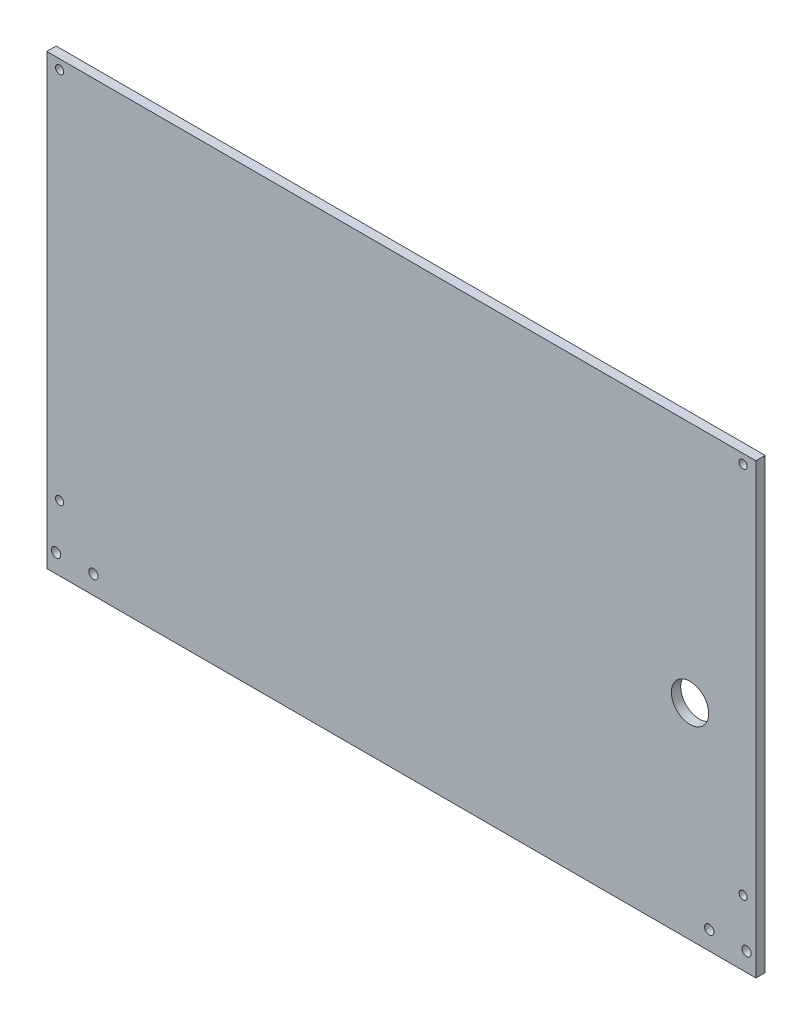
SolidWorks part; units mm, degrees
ref_plane "Front Plane" through (0, 0, 0) normal (0, 0, 1) x (1, 0, 0)
ref_plane "Top Plane" through (0, 0, 0) normal (0, 1, 0) x (1, 0, 0)
ref_plane "Right Plane" through (0, 0, 0) normal (1, 0, 0) x (0, 0, -1)
sketch "Sketch1" plane through (0, 0, 0) normal (0, 0, 1) x (1, 0, 0)
  line L1 (-241.3, -152.4) -> (241.3, -152.4)
  line L2 (-241.3, -152.4) -> (-241.3, 152.4)
  line L3 (-241.3, 152.4) -> (241.3, 152.4)
  line L4 (241.3, -152.4) -> (241.3, 152.4)
  line L5 (-241.3, -152.4) -> (241.3, 152.4) construction
  line L6 (-241.3, 152.4) -> (241.3, -152.4) construction
  point P0 (0, 0)
  dimension "D1" = 482.6
  dimension "D2" = 304.8
extrude "Boss-Extrude1" add sketch "Sketch1" along normal blind 6.35
sketch "Sketch2" plane through (0, 0, 6.35) normal (0, 0, 1) x (1, 0, 0)
  line L0 (-241.3, 0) -> (241.3, 0) construction
  line L1 (-241.3, 152.4) -> (-241.3, -152.4) construction
  line L2 (241.3, -152.4) -> (241.3, 152.4) construction
  line L3 (241.3, 152.4) -> (-241.3, 152.4) construction
  circle A0 centre (-232.5624, 146.05) radius 2.7813
  circle A1 centre (-232.5624, -107.95) radius 2.7813
  dimension "D2" = 5.5626
  dimension "D3" = 5.5626
  dimension "D1" = 8.7376
  dimension "D4" = 6.35
  dimension "D5" = 254
extrude "Cut-Extrude1" cut sketch "Sketch2" against normal through all
mirror "Mirror1" about plane through (0, 0, 0) normal (1, 0, 0) of "Cut-Extrude1"
sketch "Sketch3" plane through (0, 0, 6.35) normal (0, 0, 1) x (1, 0, 0)
  line L0 (-241.3, -139.7) -> (241.3, -139.7) construction
  line L1 (-241.3, 152.4) -> (-241.3, -152.4) construction
  line L2 (241.3, -152.4) -> (241.3, 152.4) construction
  line L3 (-241.3, -152.4) -> (241.3, -152.4) construction
  circle A0 centre (-234.95, -139.7) radius 3.175
  circle A1 centre (-209.55, -139.7) radius 3.175
  dimension "D2" = 6.35
  dimension "D3" = 6.35
  dimension "D4" = 25.4
  dimension "D5" = 6.35
  dimension "D1" = 12.7
extrude "Cut-Extrude2" cut sketch "Sketch3" against normal through all
mirror "Mirror2" about plane through (0, 0, 0) normal (1, 0, 0) of "Cut-Extrude2"
sketch "Sketch4" plane through (0, 0, 6.35) normal (0, 0, 1) x (1, 0, 0)
  line L0 (241.3, 152.4) -> (-241.3, 152.4) construction
  circle A0 centre (196.469, -12.7) radius 12.7
  dimension "D2" = 25.4
  dimension "D1" = 196.469
  dimension "D3" = 165.1
extrude "Cut-Extrude3" cut sketch "Sketch4" against normal through all
